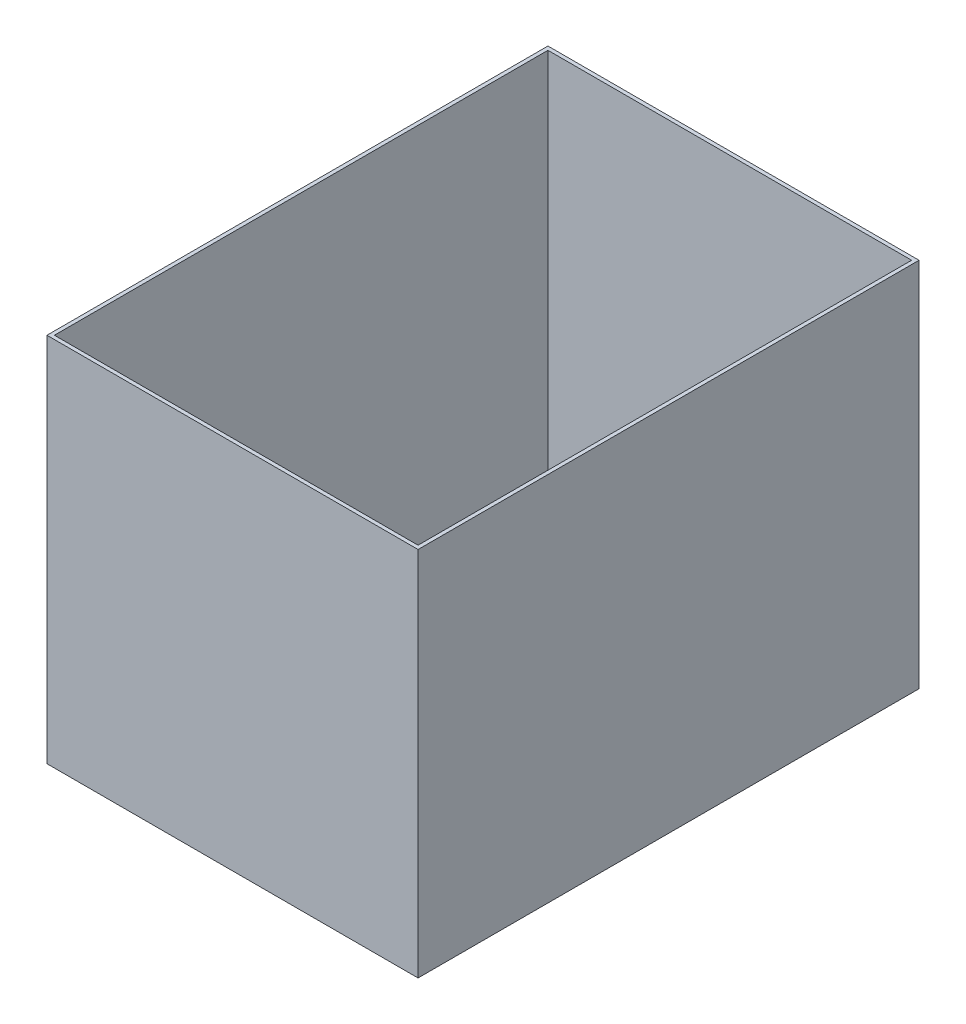
SolidWorks part; units mm, degrees
ref_plane "前视基准面" through (0, 0, 0) normal (0, 0, 1) x (1, 0, 0)
ref_plane "上视基准面" through (0, 0, 0) normal (0, 1, 0) x (1, 0, 0)
ref_plane "右视基准面" through (0, 0, 0) normal (1, 0, 0) x (0, 0, -1)
sketch "草图1" plane through (0, 0, 0) normal (0, 1, 0) x (1, 0, 0)
  line L1 (-100, 135) -> (100, 135)
  line L2 (-100, 135) -> (-100, -135)
  line L3 (-100, -135) -> (100, -135)
  line L4 (100, 135) -> (100, -135)
  line L5 (-100, 135) -> (100, -135) construction
  line L6 (-100, -135) -> (100, 135) construction
  point P0 (0, 0)
  dimension "D1" = 270
  dimension "D2" = 200
extrude "凸台-拉伸1" add sketch "草图1" along normal blind 200 contours L2 L3 L4 L1
shell "抽壳1" thickness 2
sketch "草图2" plane through (0, 0, 0) normal (0, -1, 0) x (-1, 0, 0)
  line L0 (100, -135) -> (90, -135) construction
  line L1 (100, -135) -> (-100, -135) construction
  line L2 (90, -135) -> (90, -125) construction
  line L3 (0, 0) -> (0, -50) construction
  line L4 (0, 0) -> (-50, 0) construction
  circle A0 centre (90, -125) radius 3.5
  circle A1 centre (-90, -125) radius 3.5
  circle A2 centre (-90, 125) radius 3.5
  circle A3 centre (90, 125) radius 3.5
extrude "切除-拉伸1" cut sketch "草图2" against normal blind 10
